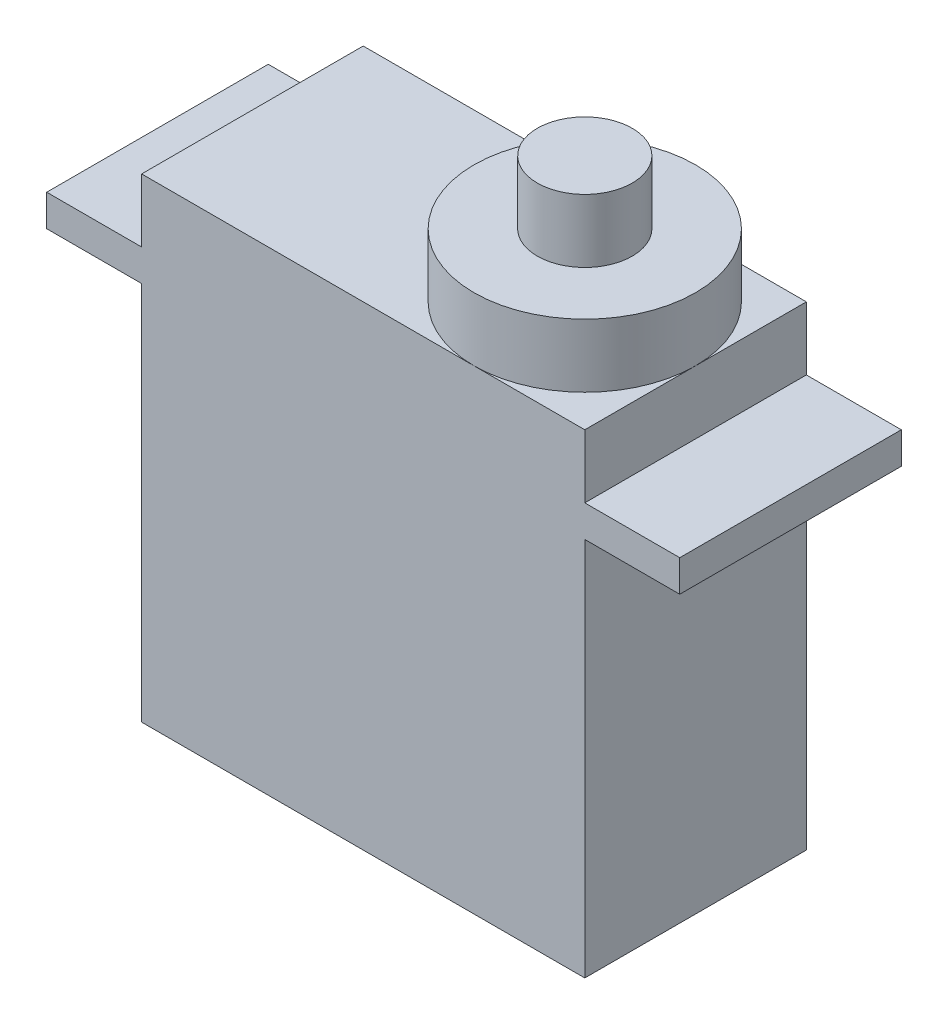
SolidWorks part; units mm, degrees
ref_plane "Front Plane" through (0, 0, 0) normal (0, 0, 1) x (1, 0, 0)
ref_plane "Top Plane" through (0, 0, 0) normal (0, 1, 0) x (1, 0, 0)
ref_plane "Right Plane" through (0, 0, 0) normal (1, 0, 0) x (0, 0, -1)
sketch "Sketch1" plane through (0, 0, 0) normal (0, 1, 0) x (1, 0, 0)
  line L0 (-11.1125, 5.5562) -> (11.1125, 5.5562)
  line L1 (-11.1125, 5.5562) -> (-11.1125, -5.5563)
  line L2 (11.1125, 5.5562) -> (11.1125, -5.5563)
  line L3 (-11.1125, -5.5563) -> (11.1125, -5.5563)
  line L4 (-11.1125, 5.5562) -> (11.1125, -5.5563) construction
  line L5 (11.1125, 5.5562) -> (-11.1125, -5.5563) construction
  point P1 (0, 0)
  dimension "D1" = 22.225
  dimension "D2" = 11.1125
extrude "Boss-Extrude1" add sketch "Sketch1" along normal blind 23.8125
sketch "Sketch2" plane through (11.1125, 0, 0) normal (1, 0, 0) x (0, 0, -1)
  line L0 (-5.5563, 20.6375) -> (5.5563, 20.6375)
  line L1 (-5.5563, 20.6375) -> (-5.5562, 19.05)
  line L2 (5.5563, 20.6375) -> (5.5563, 19.05)
  line L3 (-5.5562, 19.05) -> (5.5563, 19.05)
  line L4 (-5.5563, 20.6375) -> (5.5563, 19.05) construction
  line L5 (5.5563, 20.6375) -> (-5.5562, 19.05) construction
  line L6 (0, 23.8125) -> (0, 0) construction
  line L10 (-5.5563, 0) -> (5.5562, 0)
  line L11 (5.5562, 0) -> (5.5562, 23.8125)
  line L12 (5.5562, 23.8125) -> (-5.5563, 23.8125)
  line L13 (-5.5563, 23.8125) -> (-5.5563, 0)
  line L14 (-5.5563, 0) -> (5.5562, 0) construction
  line L15 (5.5562, 0) -> (5.5562, 23.8125) construction
  line L16 (5.5562, 23.8125) -> (-5.5563, 23.8125) construction
  line L17 (-5.5563, 23.8125) -> (-5.5563, 0) construction
  point P1 (0, 19.8437)
  dimension "D2" = 3.175
  dimension "D3" = 1.5875
  dimension "D1" = 0
extrude "Boss-Extrude2" add sketch "Sketch2" along normal blind 4.7625
ref_plane "Plane1" through (0, 0, 0) normal (-1, 0, 0) x (0, 0, 1)
mirror "Mirror2" about plane through (0, 0, 0) normal (-1, 0, 0) of "Boss-Extrude2"
sketch "Sketch3" plane through (0, 23.8125, 0) normal (0, 1, 0) x (1, 0, 0)
  line L0 (11.1125, 5.5562) -> (-11.1125, 5.5562) construction
  line L1 (-11.1125, -5.5563) -> (11.1125, -5.5563) construction
  line L5 (11.1125, -5.5563) -> (11.1125, 5.5562) construction
  circle A0 centre (5.5563, 0) radius 5.5562
extrude "Boss-Extrude3" add sketch "Sketch3" along normal blind 3.175
sketch "Sketch4" plane through (0, 26.9875, 0) normal (0, 1, 0) x (1, 0, 0)
  circle A0 centre (5.5563, 0) radius 2.3813
  circle A1 centre (5.5563, 0) radius 5.5562 construction
  dimension "D1" = 4.7625
extrude "Boss-Extrude4" add sketch "Sketch4" along normal blind 3.175
